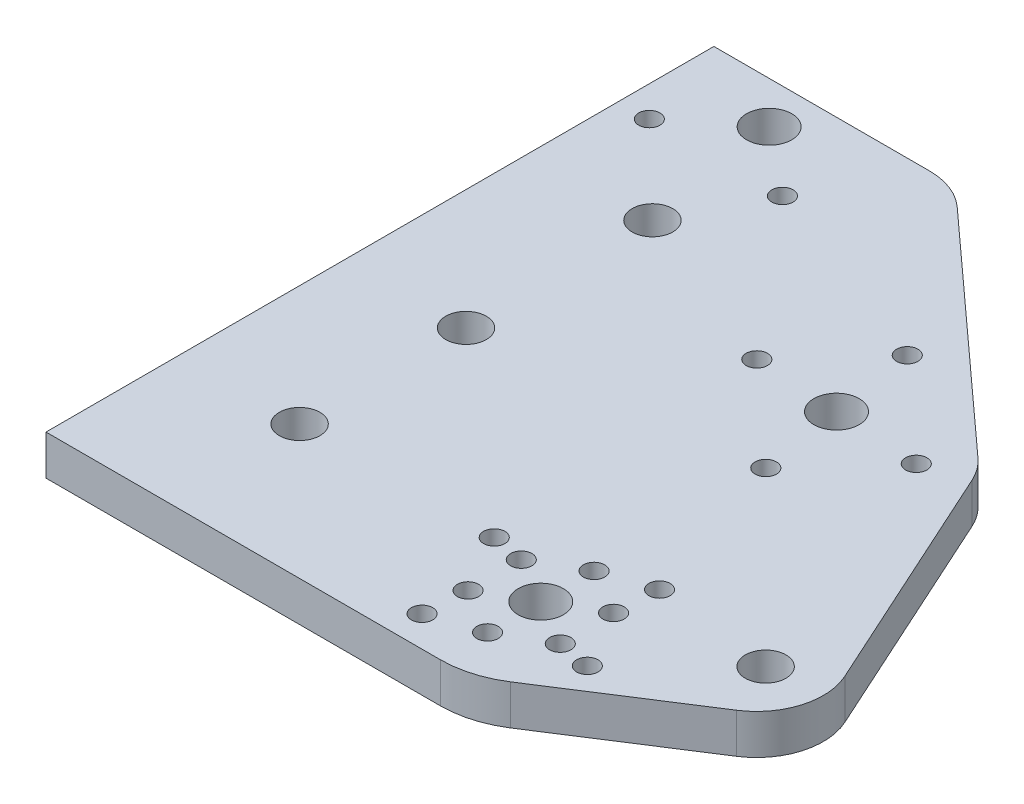
SolidWorks part; units mm, degrees
material "Policarbonato"
ref_plane "Plano frontal" through (0, 0, 0) normal (0, 0, 1) x (1, 0, 0)
ref_plane "Plano superior" through (0, 0, 0) normal (0, 1, 0) x (1, 0, 0)
ref_plane "Plano direito" through (0, 0, 0) normal (1, 0, 0) x (0, 0, -1)
ref_plane "Plano1" through (0, -6, 0) normal (0, -1, 0) x (1, 0, 0)
sketch "Esboço1" plane through (0, -6, 0) normal (0, -1, 0) x (1, 0, 0)
  line L0 (151.2357, -14.2909) -> (167.1948, 20.7865)
  line L1 (163.5005, 33.3393) -> (142.8288, 46.6294)
  line L2 (134.6661, 49.0269) -> (75.4374, 49.0269)
  line L3 (75.4374, 49.0269) -> (75.4374, -53)
  line L4 (78.4374, -56) -> (102.6847, -56)
  line L5 (109.4101, -53.4005) -> (148.859, -17.5502)
  line L6 (134.1775, -0.3541) -> (144.9383, -12.195) construction
  line L7 (144.9383, -12.195) -> (130.1372, -25.6459) construction
  line L8 (130.1372, -25.6459) -> (119.3765, -13.805) construction
  line L9 (119.3765, -13.805) -> (134.1775, -0.3541) construction
  line L10 (134.1775, -0.3541) -> (130.1372, -25.6459) construction
  line L11 (100.0374, -37) -> (80.0374, -53) construction
  line L12 (127.326, 44.4269) -> (146.5154, 38.7906) construction
  line L13 (146.5154, 38.7906) -> (142.0063, 23.4391) construction
  line L14 (142.0063, 23.4391) -> (122.8169, 29.0754) construction
  line L15 (122.8169, 29.0754) -> (127.326, 44.4269) construction
  line L16 (127.326, 44.4269) -> (142.0063, 23.4391) construction
  line L17 (134.6661, 33.933) -> (138.9199, 48.4151) construction
  line L18 (75.4374, -51.3) -> (111.7215, -51.3)
  circle A0 centre (119.3765, -13.805) radius 1.6
  circle A1 centre (146.5154, 38.7906) radius 1.6
  circle A2 centre (142.0063, 23.4391) radius 1.6
  circle A3 centre (159.9953, 25.4877) radius 3.05
  circle A4 centre (100.0374, -37) radius 1.6
  circle A5 centre (100.0374, -53) radius 1.6
  circle A6 centre (80.0374, -37) radius 1.6
  circle A7 centre (80.0374, -53) radius 1.6
  circle A8 centre (122.8169, 29.0754) radius 1.6
  circle A9 centre (127.326, 44.4269) radius 1.6
  circle A10 centre (130.1372, -25.6459) radius 1.6
  circle A11 centre (144.9383, -12.195) radius 1.6
  circle A12 centre (134.1775, -0.3541) radius 1.6
  circle A13 centre (141.5943, 29.933) radius 1.6
  circle A14 centre (134.6661, 25.933) radius 1.6
  circle A15 centre (127.7379, 29.933) radius 1.6
  circle A16 centre (127.7379, 37.933) radius 1.6
  circle A17 centre (134.6661, 41.933) radius 1.6
  circle A18 centre (141.5943, 37.933) radius 1.6
  circle A19 centre (134.6661, 33.933) radius 3.4
  circle A20 centre (132.1574, -13) radius 3.4
  circle A21 centre (90.0374, -45) radius 3.4
  arc A22 (167.1948, 20.7865) -> (163.5005, 33.3393) centre (158.0926, 24.9277) ccw
  arc A23 (142.8288, 46.6294) -> (134.6661, 49.0269) centre (134.6661, 33.933) ccw
  arc A24 (75.4374, -53) -> (78.4374, -56) centre (78.4374, -53) ccw
  arc A25 (102.6847, -56) -> (109.4101, -53.4005) centre (102.6847, -46) ccw
  arc A26 (148.859, -17.5502) -> (151.2357, -14.2909) centre (142.1335, -10.1497) ccw
  arc A27 (107.8564, -51.3) -> (114.5819, -48.7005) centre (107.8564, -41.3) ccw
  point P62 (134.6661, 33.933)
  dimension "D4" = 10
  dimension "D5" = 6.1
  dimension "D8" = 6.8
  dimension "D9" = 3.2
  dimension "D24" = 3
  dimension "D1" = 105.0269
  dimension "D2" = 11
  dimension "D3" = 82.6552
  dimension "D6" = 80.9277
  dimension "D7" = 137.736
  dimension "D10" = 20
  dimension "D11" = 16
  dimension "D12" = 6.6
  dimension "D13" = 52.897
  dimension "D14" = 43
  dimension "D15" = 16
  dimension "D16" = 90.676
  dimension "D17" = 59.2287
  dimension "D18" = 14.6
  dimension "D19" = 8
  dimension "D21" = 26.7
  dimension "D22" = 47.5
  dimension "D23" = 6.6
  dimension "D25" = 4.7
  dimension "D20" = 6
extrude "Ressalto-extrusão1" add sketch "Esboço1" against normal blind 6 contours L18 A27 L5 A26 L0 A22 L1 A23 L2 L3 A21 A19 A17 A15 A13 A11 A9 A3 A1 A0 A2 A4 A6 A8 A10 A12 A14 A16 A18 A20
sketch "Esboço2" plane through (0, -6, 0) normal (0, -1, 0) x (1, 0, 0)
  line L0 (75.4374, 49.0269) -> (75.4374, -51.3) construction
  line L1 (71.813, 11.433) -> (140.3089, 11.433) construction
  circle A0 centre (93.4374, 3.933) radius 3.05
  circle A1 centre (93.4374, -24.067) radius 3.05
  circle A2 centre (93.4374, 3.933) radius 7.5 construction
  circle A3 centre (93.4374, -24.067) radius 7.5 construction
  circle A4 centre (93.4374, 28.933) radius 3.05
  circle A5 centre (134.6661, 33.933) radius 3.4 construction
  point P16 (0, 0)
  dimension "D1" = 6.1
  dimension "D2" = 15
  dimension "D3" = 25
  dimension "D5" = 30
  dimension "D6" = 28
  dimension "D4" = 18
extrude "Corte-extrusão1" cut sketch "Esboço2" against normal blind 10 contours A1 | A0 | A4
